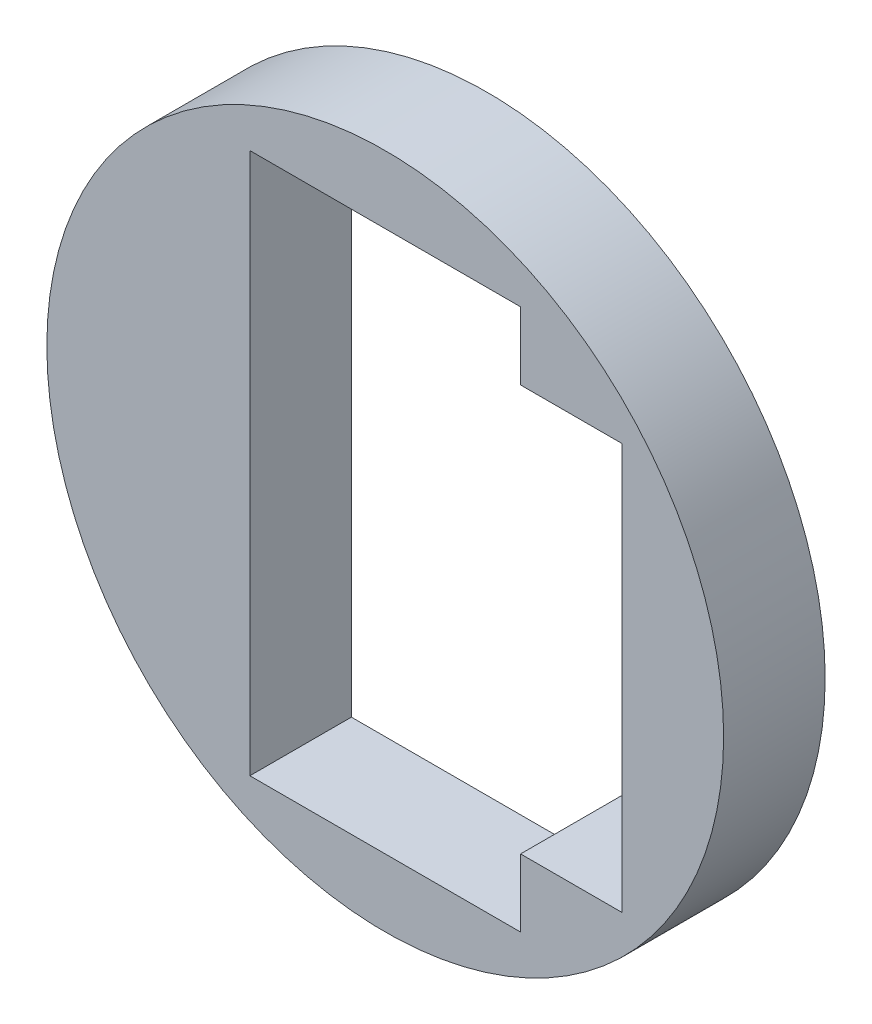
SolidWorks part; units mm, degrees
ref_plane "Front Plane" through (0, 0, 0) normal (0, 0, 1) x (1, 0, 0)
ref_plane "Top Plane" through (0, 0, 0) normal (0, 1, 0) x (1, 0, 0)
ref_plane "Right Plane" through (0, 0, 0) normal (1, 0, 0) x (0, 0, -1)
sketch "Sketch1" plane through (0, 0, 0) normal (0, 0, 1) x (1, 0, 0)
  circle A0 centre (0, 0) radius 10
  dimension "D1" = 20
extrude "Boss-Extrude1" add sketch "Sketch1" along normal blind 3
sketch "Sketch2" plane through (0, 0, 3) normal (0, 0, 1) x (1, 0, 0)
  line L0 (-4, 8) -> (-4, -8)
  line L1 (-4, -8) -> (4, -8)
  line L2 (4, -8) -> (4, -6)
  line L3 (4, -6) -> (7, -6)
  line L4 (7, -6) -> (7, 6)
  line L5 (7, 6) -> (4, 6)
  line L6 (4, 6) -> (4, 8)
  line L7 (4, 8) -> (-4, 8)
  circle A0 centre (0, 0) radius 10 construction
  point P11 (-4.1708, 8)
  dimension "D1" = 8
  dimension "D2" = 16
  dimension "D3" = 8
  dimension "D4" = 4
  dimension "D5" = 12
  dimension "D6" = 3
extrude "Cut-Extrude1" cut sketch "Sketch2" against normal through all
